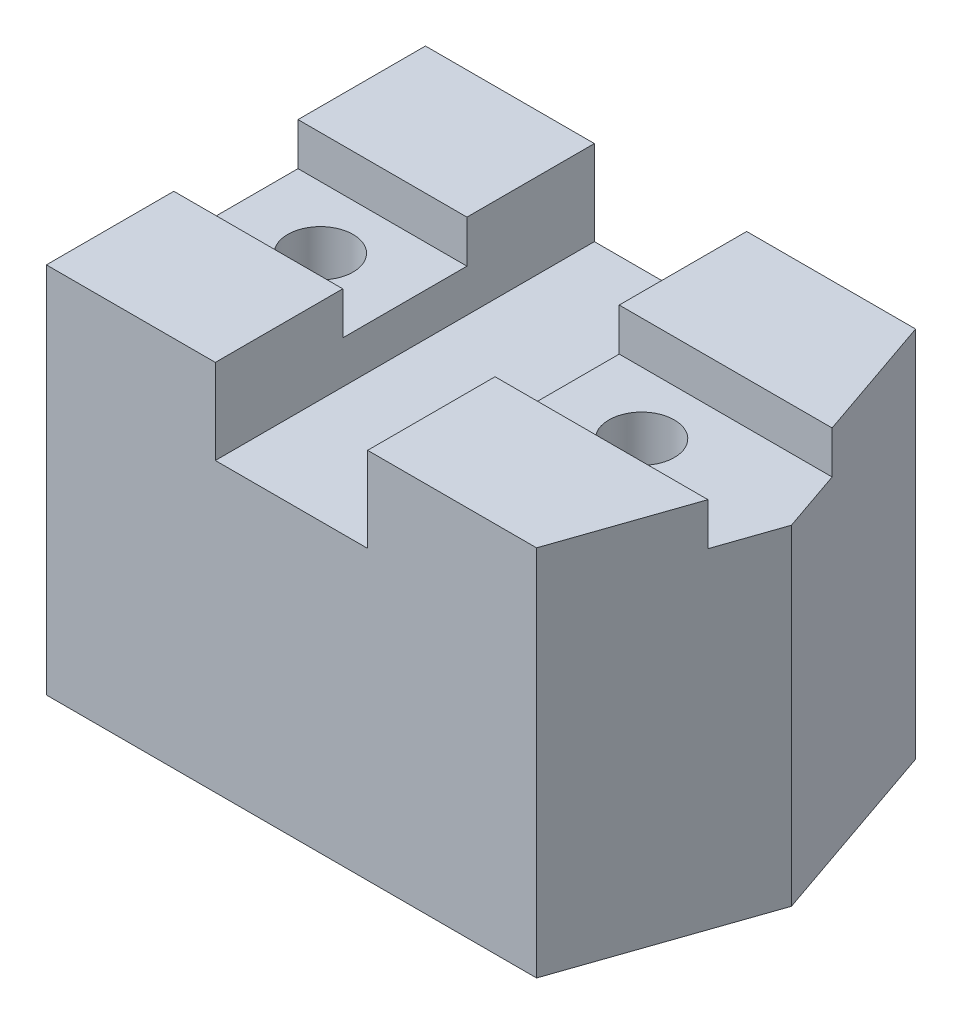
SolidWorks part; units mm, degrees
ref_plane "Piano frontale" through (0, 0, 0) normal (0, 0, 1) x (1, 0, 0)
ref_plane "Piano superiore" through (0, 0, 0) normal (0, 1, 0) x (1, 0, 0)
ref_plane "Piano destro" through (0, 0, 0) normal (1, 0, 0) x (0, 0, -1)
sketch "Schizzo1" plane through (0, 0, 0) normal (0, 1, 0) x (1, 0, 0)
  line L0 (-156.0125, 0) -> (182.9739, 0) construction
  line L1 (-107.155, -58) -> (-107.155, 58)
  line L2 (-107.155, 58) -> (42.845, 58)
  line L3 (42.845, 58) -> (62.845, 0)
  line L4 (42.845, -58) -> (62.845, 0)
  line L5 (-107.155, -58) -> (42.845, -58)
  point P9 (-107.155, 0)
  dimension "D1" = 116
  dimension "D2" = 150
  dimension "D3" = 170
extrude "Estrusione-Estrusione1" add sketch "Schizzo1" along normal blind 114
sketch "Schizzo3" plane through (0, 114, 0) normal (0, 1, 0) x (1, 0, 0)
  line L0 (62.845, 0) -> (-107.155, 0) construction
  line L1 (-107.155, 58) -> (-107.155, -58) construction
  line L2 (-107.155, -19) -> (-107.155, 19)
  line L3 (-107.155, 19) -> (56.2933, 19)
  line L4 (62.845, 0) -> (42.845, 58) construction
  line L5 (56.2933, 19) -> (62.845, 0)
  line L6 (56.2933, -19) -> (62.845, 0)
  line L7 (-107.155, -19) -> (56.2933, -19)
  dimension "D1" = 38
extrude "Taglio-Estrusione3" cut sketch "Schizzo3" against normal blind 13
sketch "Schizzo6" plane through (0, 114, 0) normal (0, 1, 0) x (1, 0, 0)
  line L0 (-32.155, 58) -> (-32.155, -58) construction
  line L1 (42.845, 58) -> (-107.155, 58) construction
  line L2 (-107.155, -58) -> (42.845, -58) construction
  line L3 (-55.456, -58) -> (-8.854, -58)
  line L4 (-8.854, -58) -> (-8.854, 58)
  line L5 (-8.854, 58) -> (-55.456, 58)
  line L6 (-55.456, -58) -> (-55.456, 58)
extrude "Taglio-Estrusione4" cut sketch "Schizzo6" against normal blind 26
sketch "Schizzo7" plane through (0, 101, 0) normal (0, 1, 0) x (1, 0, 0)
  line L0 (-107.155, 0) -> (-55.456, 0) construction
  line L1 (-107.155, 19) -> (-107.155, -19) construction
  line L2 (-55.456, -19) -> (-55.456, 19) construction
  line L3 (-81.3055, 19) -> (-81.3055, -19) construction
  line L4 (-55.456, 19) -> (-107.155, 19) construction
  line L5 (-107.155, -19) -> (-55.456, -19) construction
  line L6 (-55.456, 0) -> (-8.854, 0) construction
  line L7 (-8.854, 19) -> (-8.854, -19) construction
  line L8 (-32.155, 105.8564) -> (-32.155, -105.8564) construction
  circle A0 centre (-81.3055, 0) radius 10
  circle A1 centre (16.9955, 0) radius 10
  point P20 (-32.155, 0)
extrude "Taglio-Estrusione5" cut sketch "Schizzo7" against normal through all
